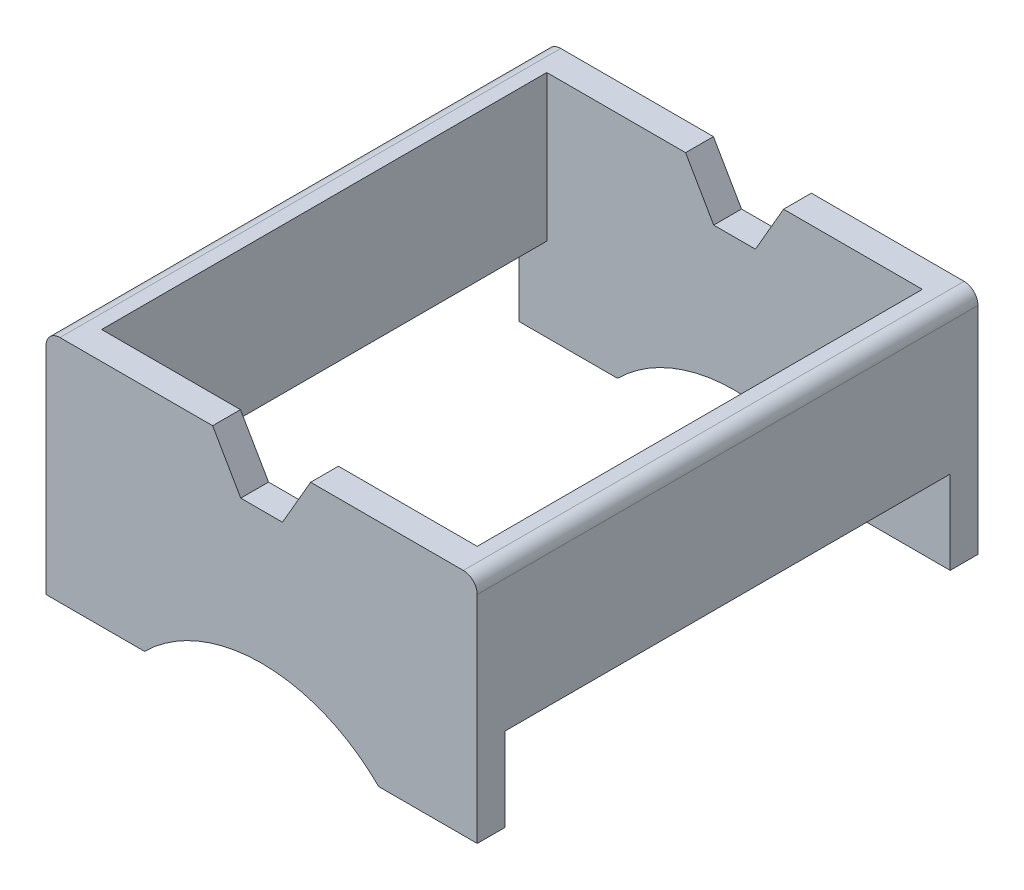
SolidWorks part; units mm, degrees
material "Cast Stainless Steel"
ref_plane "Front Plane" through (0, 0, 0) normal (0, 0, 1) x (1, 0, 0)
ref_plane "Top Plane" through (0, 0, 0) normal (0, 1, 0) x (1, 0, 0)
ref_plane "Right Plane" through (0, 0, 0) normal (1, 0, 0) x (0, 0, -1)
other "Configuration Table"
sketch "Sketch1" plane through (0, 0, 0) normal (0, 1, 0) x (1, 0, 0)
  line L0 (15.5, 18) -> (-15.5, -18) construction
  line L1 (-15.5, 18) -> (15.5, 18)
  line L2 (-15.5, 18) -> (-15.5, -18)
  line L3 (-15.5, -18) -> (15.5, -18)
  line L4 (15.5, 18) -> (15.5, -18)
  line L5 (-15.5, -18) -> (-16.2586, -16.9886) construction
  line L6 (13.5, 16) -> (13.5, -16)
  line L7 (-13.5, -16) -> (13.5, -16)
  line L8 (-13.5, 16) -> (-13.5, -16)
  line L9 (-13.5, 16) -> (13.5, 16)
  point P4 (0, 0)
  dimension "D1" = 31
  dimension "D2" = 36
  dimension "D3" = 2
extrude "Extrude1" add sketch "Sketch1" along normal blind 16.5
sketch "Sketch2" plane through (-15.5, 0, 0) normal (-1, 0, 0) x (0, 0, 1)
  line L1 (-16, 6) -> (16, 6)
  line L2 (-16, 6) -> (-16, 0)
  line L3 (-16, 0) -> (16, 0)
  line L4 (16, 6) -> (16, 0)
  line L6 (-18, 0) -> (18, 0) construction
  line L7 (0, 0) -> (0, 12.8111) construction
  line L8 (16, 16.5) -> (16, 0) construction
  point P8 (0, 6)
  dimension "D2" = 6
extrude "Cut-Extrude1" cut sketch "Sketch2" against normal through all
sketch "Sketch3" plane through (0, 0, -18) normal (0, 0, -1) x (-1, 0, 0)
  line L0 (0, 0) -> (0, 17.9755) construction
  line L2 (-3.5207, 16.5) -> (3.5207, 16.5)
  line L3 (3.5207, 16.5) -> (1.5, 13)
  line L4 (-3.5207, 16.5) -> (-1.5, 13)
  line L5 (1.5, 13) -> (-1.5, 13)
  line L6 (-15.5, 16.5) -> (15.5, 16.5) construction
  point P4 (0, 16.5)
  dimension "D1" = 60
  dimension "D2" = 1.5
  dimension "D3" = 3.5
extrude "Cut-Extrude2" cut sketch "Sketch3" against normal through all
fillet "Fillet1" radius 1 2 edges at (15.5, 16.5, 0) (-15.5, 16.5, 0)
sketch "Sketch4" plane through (0, 0, -18) normal (0, 0, -1) x (-1, 0, 0)
  line L0 (-15.5, 0) -> (15.5, 0) construction
  arc A0 (-8.416, 0) -> (8.416, 0) centre (0, -8.4572) cw
extrude "Cut-Extrude4" cut sketch "Sketch4" against normal through all and the other way through all flip side to cut
